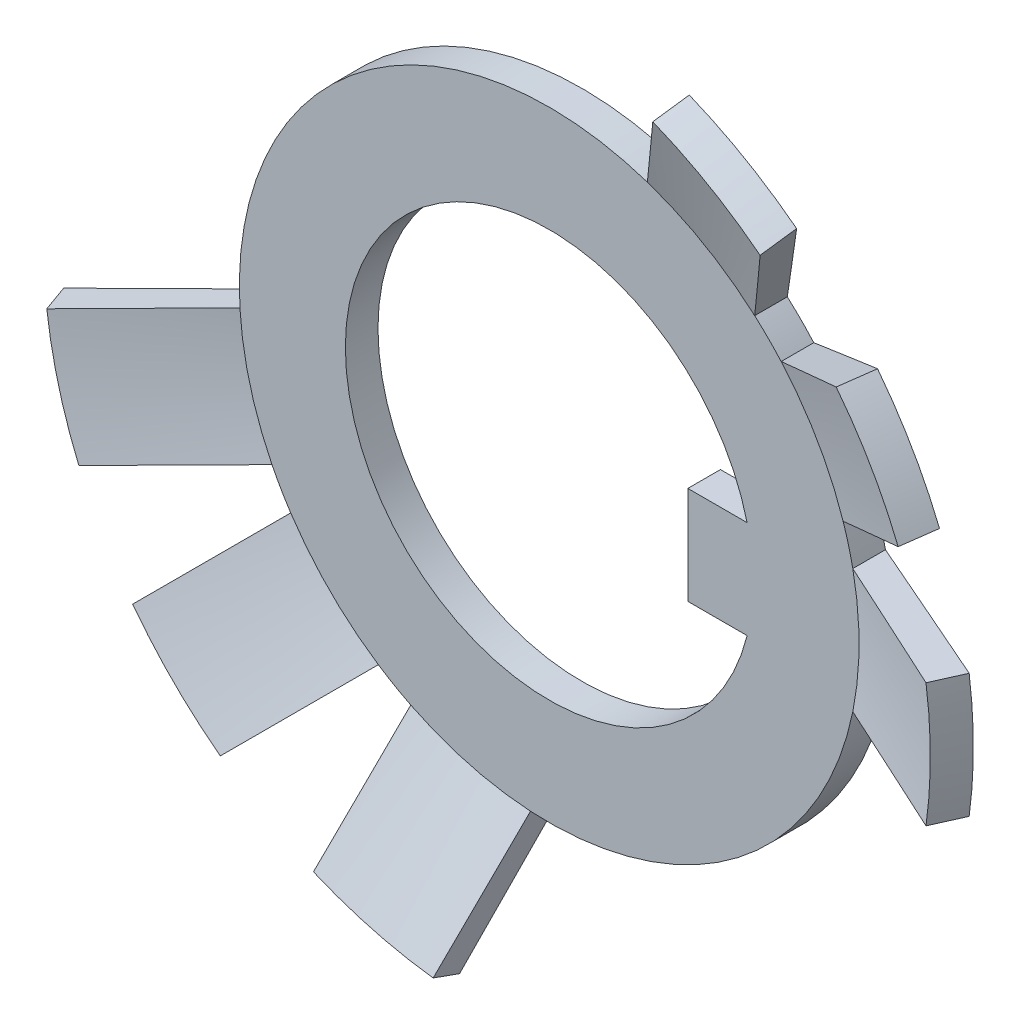
SolidWorks part; units mm, degrees
ref_plane "Front" through (0, 0, 0) normal (0, 0, 1) x (1, 0, 0)
ref_plane "Top" through (0, 0, 0) normal (0, 1, 0) x (1, 0, 0)
ref_plane "Right" through (0, 0, 0) normal (1, 0, 0) x (0, 0, -1)
sketch "Sketch1" plane through (0, 0, 0) normal (1, 0, 0) x (0, 1, 0)
  line L0 (0, -2.9094) -> (-9.5, -2.9094)
  line L1 (-9.5, -2.9094) -> (-14, -0.9142)
  line L2 (0, 5.8236) -> (0, -8.1378) construction
  line L4 (-13.5947, 0) -> (-9.5, -1.9094)
  line L5 (-9.5, -1.9094) -> (0, -1.9094)
  line L6 (0, -1.9094) -> (0, -2.9094)
  line L7 (-14, -0.9142) -> (-13.5947, 0)
  dimension "D1" = 19
  dimension "S1" = 1
  dimension "Angle" = 65
  dimension "D" = 28
  dimension "S" = 1
revolve "Base-Extrude" add sketch "Sketch1" angle 360 about L2
sketch "Sketch2" plane through (-2.4044, 1.0036, -2.9094) normal (0, 0, -1) x (-1, 0, 0)
  line L0 (-8.4717, 0.4964) -> (-6.6544, 0.4964)
  line L1 (-6.6544, 0.4964) -> (-6.6544, -2.5036)
  line L2 (-6.6544, -2.5036) -> (-8.4717, -2.5036)
  line L3 (-11.7124, -2.9036) -> (-16.2748, -2.9036)
  line L4 (-11.7124, 0.8964) -> (-16.2748, 0.8964)
  line L5 (-9.5154, 5.2959) -> (-13.4665, 7.5771)
  line L6 (-11.4154, 2.005) -> (-15.3665, 4.2862)
  line L7 (-5.4129, 8.0074) -> (-7.6941, 11.9586)
  line L8 (-8.7038, 6.1074) -> (-10.985, 10.0586)
  line L9 (-2.4044, 13.9688) -> (-2.4044, -17.023) construction
  line L10 (-2.4044, -1.0036) -> (1.5148, -15.6299) construction
  line L11 (-1.8305, -10.4862) -> (-0.6497, -14.8932)
  line L12 (1.84, -9.5027) -> (3.0208, -13.9097)
  line L13 (5.5209, -6.2419) -> (8.7471, -9.468)
  line L14 (2.8339, -8.9289) -> (6.06, -12.155)
  line L15 (7.0783, -1.5774) -> (11.4853, -2.7583)
  line L16 (6.0948, -5.2479) -> (10.5017, -6.4288)
  line L17 (-2.4044, -1.0036) -> (-1.8305, -10.4862) construction
  arc A0 (-8.4717, -2.5036) -> (-8.4717, 0.4964) centre (-2.4044, -1.0036) ccw
  circle A1 centre (-2.4044, -1.0036) radius 9.5 construction
  arc A2 (-11.7124, -2.9036) -> (-1.8305, -10.4862) centre (-2.4044, -1.0036) ccw
  arc A4 (-13.4665, 7.5771) -> (-15.3665, 4.2862) centre (-2.4044, -1.0036) ccw
  arc A5 (-8.7038, 6.1074) -> (-9.5154, 5.2959) centre (-2.4044, -1.0036) ccw
  arc A6 (-11.4154, 2.005) -> (-11.7124, 0.8964) centre (-2.4044, -1.0036) ccw
  arc A7 (-16.2748, 0.8964) -> (-16.2748, -2.9036) centre (-2.4044, -1.0036) ccw
  arc A8 (-7.6941, 11.9586) -> (-10.985, 10.0586) centre (-2.4044, -1.0036) ccw
  arc A9 (-0.6497, -14.8932) -> (3.0208, -13.9097) centre (-2.4044, -1.0036) ccw
  arc A10 (6.06, -12.155) -> (8.7471, -9.468) centre (-2.4044, -1.0036) ccw
  arc A11 (10.5017, -6.4288) -> (11.4853, -2.7583) centre (-2.4044, -1.0036) ccw
  arc A12 (7.0783, -1.5774) -> (-5.4129, 8.0074) centre (-2.4044, -1.0036) ccw
  arc A13 (5.5209, -6.2419) -> (6.0948, -5.2479) centre (-2.4044, -1.0036) ccw
  arc A14 (1.84, -9.5027) -> (2.8339, -8.9289) centre (-2.4044, -1.0036) ccw
  circle A16 centre (-2.4044, -1.0036) radius 14 construction
  dimension "d" = 12.5
  dimension "b1" = 3
  dimension "b2" = 1.5
  dimension "a" = 10.5
  dimension "D6" = 3.8
  dimension "D7" = 1.9
  dimension "D8" = 30
  dimension "D9" = 15
  dimension "b" = 3.8
  dimension "D11" = 1.9
  dimension "D2" = 30
extrude "Cut-Extrude" cut sketch "Sketch2" against normal through all flip side to cut
equation "\"D11@Sketch2\" = \"b@Sketch2\" / 2"
equation "\"D6@Sketch2\" = \"b@Sketch2\""
equation "\"D7@Sketch2\" = \"b@Sketch2\" / 2"
equation "\"S1@Sketch1\" = \"S@Sketch1\""
